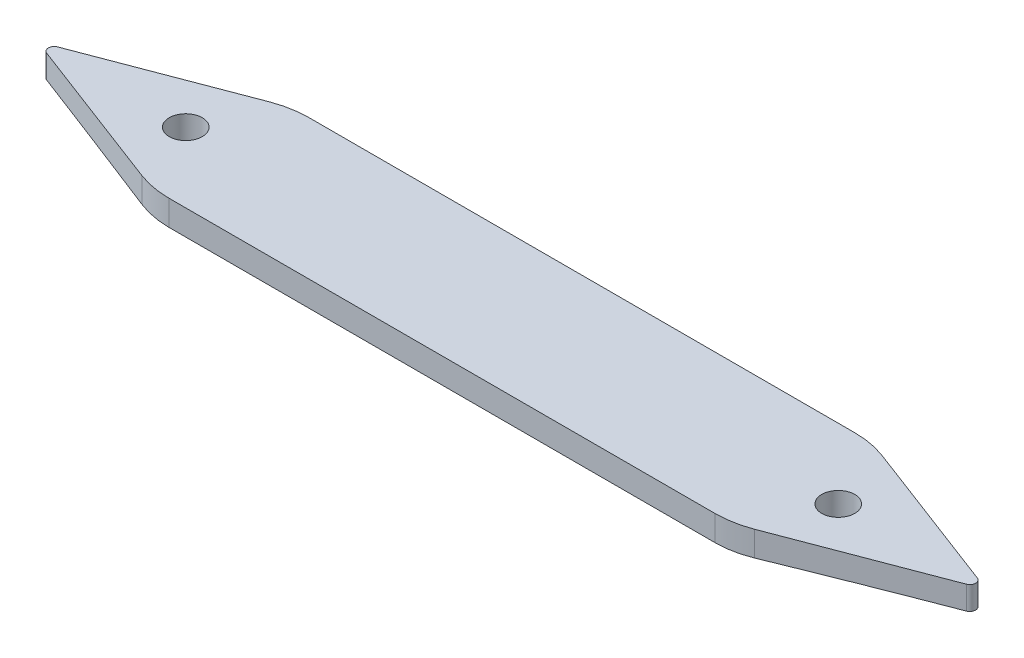
SolidWorks part; units mm, degrees
ref_plane "Front Plane" through (0, 0, 0) normal (0, 0, 1) x (1, 0, 0)
ref_plane "Top Plane" through (0, 0, 0) normal (0, 1, 0) x (1, 0, 0)
ref_plane "Right Plane" through (0, 0, 0) normal (1, 0, 0) x (0, 0, -1)
sketch "Sketch1" plane through (0, 0, 0) normal (0, 1, 0) x (1, 0, 0)
  line L0 (-119.3628, 0) -> (111.8082, 0) construction
  line L1 (0, 90.7812) -> (0, -92.2921) construction
  line L2 (37.205, 9.525) -> (-37.205, 9.525)
  line L3 (-41.7162, 8.6968) -> (-62.6498, 0.742)
  line L4 (37.205, -9.525) -> (-37.205, -9.525)
  line L5 (-41.7162, -8.6968) -> (-62.6498, -0.742)
  line L6 (41.7162, -8.6968) -> (62.6498, -0.742)
  line L7 (41.7162, 8.6968) -> (62.6498, 0.742)
  arc A0 (-37.205, 9.525) -> (-41.7162, 8.6968) centre (-37.205, -3.175) ccw
  arc A1 (-37.205, -9.525) -> (-41.7162, -8.6968) centre (-37.205, 3.175) cw
  arc A2 (-62.6498, -0.742) -> (-62.6498, 0.742) centre (-62.3679, 0) cw
  arc A3 (37.205, -9.525) -> (41.7162, -8.6968) centre (37.205, 3.175) ccw
  arc A4 (62.6498, -0.742) -> (62.6498, 0.742) centre (62.3679, 0) ccw
  arc A5 (37.205, 9.525) -> (41.7162, 8.6968) centre (37.205, -3.175) cw
  point P6 (-64.6024, 0)
  point P18 (0, -9.525)
  point P26 (0, 9.525)
  dimension "D1" = 12.7
  dimension "D2" = 0.7937
  dimension "D3" = 19.05
extrude "Boss-Extrude2" add sketch "Sketch1" along normal blind 22.225 and the other way blind 10
sketch "Sketch2" plane through (0, 0, 9.525) normal (0, 0, 1) x (1, 0, 0)
  line L0 (-37.205, 22.225) -> (37.205, 22.225) construction
  line L1 (-68.6771, 15.875) -> (84.4664, 15.875)
  line L2 (-68.6771, 15.875) -> (-68.6771, 9.525)
  line L3 (-68.6771, 9.525) -> (84.4664, 9.525)
  line L4 (84.4664, 15.875) -> (84.4664, 9.525)
  dimension "D1" = 6.35
  dimension "D2" = 6.35
extrude "Cut-Extrude1" cut sketch "Sketch2" against normal blind 4.7625
sketch "Sketch3" plane through (0, 0, -9.525) normal (0, 0, -1) x (-1, 0, 0)
  line L0 (-37.205, 22.225) -> (37.205, 22.225) construction
  line L1 (-67.7785, 15.875) -> (84.9799, 15.875)
  line L2 (-67.7785, 15.875) -> (-67.7785, 9.525)
  line L3 (-67.7785, 9.525) -> (84.9799, 9.525)
  line L4 (84.9799, 15.875) -> (84.9799, 9.525)
  dimension "D1" = 6.35
  dimension "D2" = 6.35
extrude "Cut-Extrude2" cut sketch "Sketch3" against normal blind 4.7625
fillet "Fillet3" radius 12.7 1 edges at (52.0695, 12.7, -4.7625)
fillet "Fillet4" radius 12.7 1 edges at (52.0695, 12.7, 4.7625)
fillet "Fillet5" radius 12.7 1 edges at (-52.0695, 12.7, 4.7625)
fillet "Fillet6" radius 12.7 1 edges at (-52.0695, 12.7, -4.7625)
sketch "Sketch12" plane through (0, 0, 0) normal (1, 0, 0) x (0, 0, -1)
  circle A0 centre (0, -168.402) radius 168.402
extrude "Cut-Extrude3" cut sketch "Sketch12" against normal blind 84.675 and the other way blind 94.675
sketch "Sketch19" plane through (0, 22.225, 0) normal (0, 1, 0) x (1, 0, 0)
  point P0 (-44.45, 0)
  point P1 (44.45, 0)
hole_wizard "CSK for #8 Flat Head Socket Cap Screw2" positions "Sketch21" profile "Sketch20" countersink size "#8" standard "ANSI Inch" end condition through all
sketch "Sketch21" plane through (0, 22.225, 0) normal (0, 1, 0) x (1, 0, 0)
  point P0 (-44.45, 0)
  point P3 (44.45, 0)
sketch "Sketch20" plane through (-44.45, 22.225, 0) normal (1, 0, 0) x (0, 0, 1)
  line L0 (0, 0) -> (0, 23.3241)
  line L1 (0, 23.3241) -> (2.2479, 23.3241)
  line L2 (2.2479, 23.3241) -> (2.2479, 2.659)
  line L3 (2.2479, 2.659) -> (4.5593, 0)
  line L5 (4.5593, 0) -> (0, 0)
  line L6 (-2.2479, 2.659) -> (-4.5593, 0) construction
  line L11 (0, -6.35) -> (0, 107.95) construction
  dimension "Thru Hole Dia." = 4.4958
  dimension "Thru Hole Depth" = 23.3241
  dimension "Near C'Sink Dia." = 9.1186
  dimension "Near C'Sink Angle" = 82
ref_plane "Plane6" through (0, 3.175, 0) normal (0, 1, 0) x (1, 0, 0)
sketch "Sketch22" plane through (0, 3.175, 0) normal (0, 1, 0) x (1, 0, 0)
  line L1 (-73.5642, 11.9434) -> (71.0724, 11.9434)
  line L2 (-73.5642, 11.9434) -> (-73.5642, -12.0984)
  line L3 (-73.5642, -12.0984) -> (71.0724, -12.0984)
  line L4 (71.0724, 11.9434) -> (71.0724, -12.0984)
extrude "Cut-Extrude4" cut sketch "Sketch22" along normal blind 42.672
